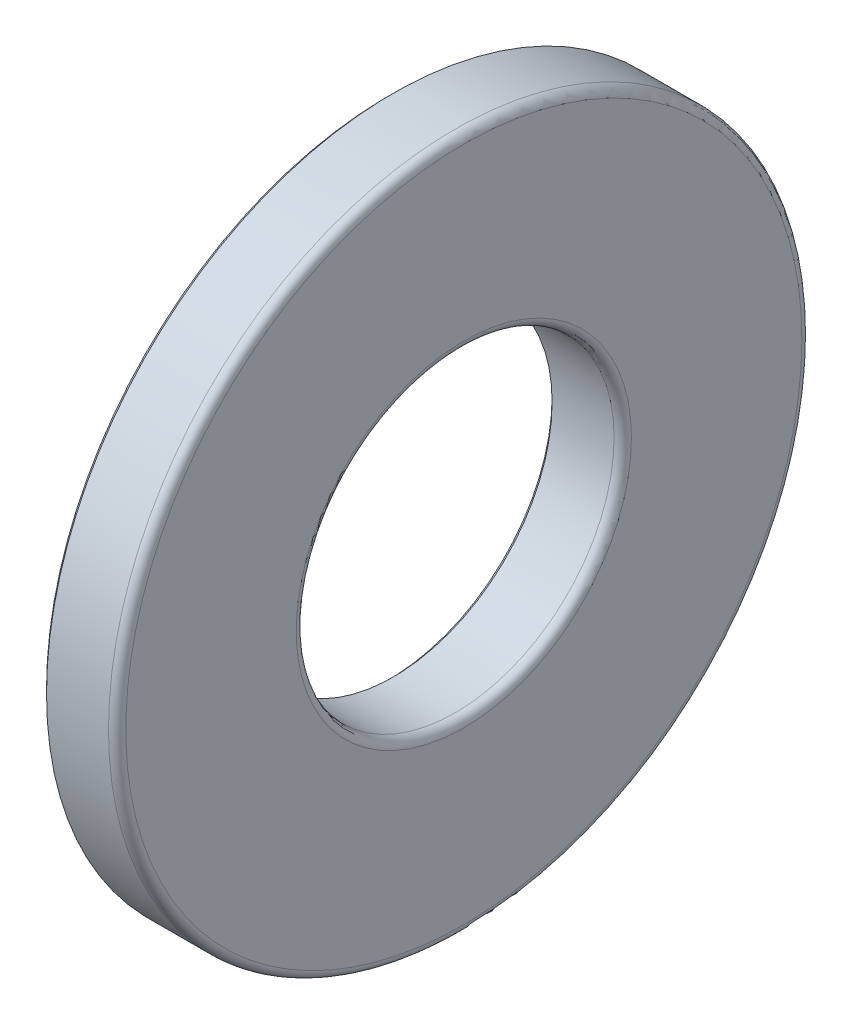
SolidWorks part; units mm, degrees
ref_plane "Спереди" through (0, 0, 0) normal (0, 0, 1) x (1, 0, 0)
ref_plane "Сверху" through (0, 0, 0) normal (0, 1, 0) x (1, 0, 0)
ref_plane "Справа" through (0, 0, 0) normal (1, 0, 0) x (0, 0, -1)
sketch "Эскиз1" plane through (0, 0, 0) normal (0, 0, 1) x (1, 0, 0)
  line L0 (6.4048, 12) -> (6.4048, 9.9286)
  line L1 (6.4048, 7.0714) -> (6.4048, 5.5)
  line L2 (6.4048, 5.5) -> (8.7, 5.5)
  line L3 (9, 5.8) -> (9, 11.7)
  line L4 (8.7, 12) -> (6.4048, 12)
  line L5 (6.4048, 0) -> (9.0013, 0) construction
  arc A0 (6.4048, 9.9286) -> (6.4048, 7.0714) centre (4.5, 8.5) cw
  arc A1 (8.7, 5.5) -> (9, 5.8) centre (8.7, 5.8) ccw
  arc A2 (9, 11.7) -> (8.7, 12) centre (8.7, 11.7) ccw
revolve "Повернуть1" add sketch "Эскиз1" angle 360 about L5
chamfer "Фаска1" distance 0.15 angle 45 2 edges at (6.4048, 0, -5.5) (6.4048, 0, -12)
